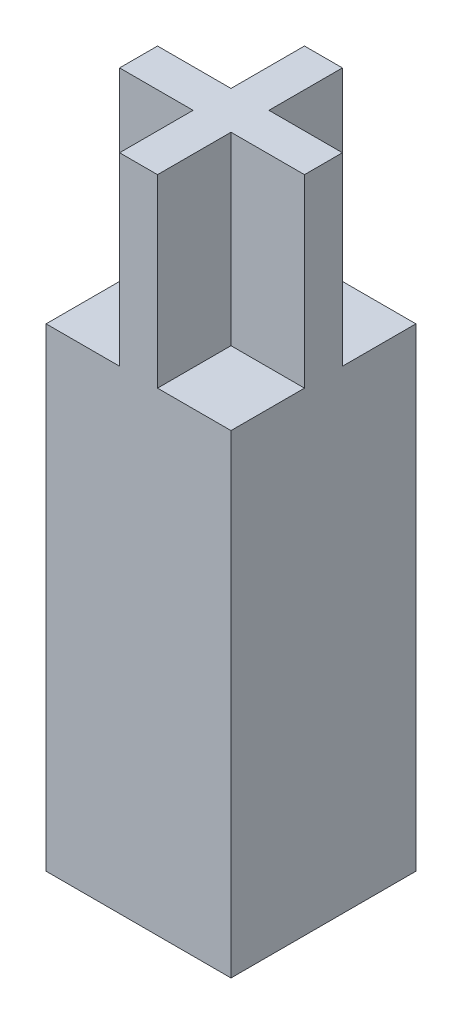
SolidWorks part; units mm, degrees
ref_plane "前视基准面" through (0, 0, 0) normal (0, 0, 1) x (1, 0, 0)
ref_plane "上视基准面" through (0, 0, 0) normal (0, 1, 0) x (1, 0, 0)
ref_plane "右视基准面" through (0, 0, 0) normal (1, 0, 0) x (0, 0, -1)
other "Configuration Table"
sketch "草图5" plane through (0, 0, 0) normal (0, 1, 0) x (-1, 0, 0)
  line L1 (-0.4, -1.95) -> (0.4, -1.95)
  line L2 (-0.4, -1.95) -> (-0.4, 1.95)
  line L3 (-0.4, 1.95) -> (0.4, 1.95)
  line L4 (0.4, -1.95) -> (0.4, 1.95)
  line L5 (-0.4, -1.95) -> (0.4, 1.95) construction
  line L6 (-0.4, 1.95) -> (0.4, -1.95) construction
  line L7 (-1.95, -0.4) -> (1.95, -0.4)
  line L8 (-1.95, -0.4) -> (-1.95, 0.4)
  line L9 (-1.95, 0.4) -> (1.95, 0.4)
  line L10 (1.95, -0.4) -> (1.95, 0.4)
  line L11 (-1.95, -0.4) -> (1.95, 0.4) construction
  line L12 (-1.95, 0.4) -> (1.95, -0.4) construction
  point P0 (0, 0)
  point P6 (0, 0)
  dimension "D1" = 3.9
  dimension "D2" = 0.8
extrude "凸台-拉伸1" add sketch "草图5" along normal blind 3.9 contours L7 L10 L9 L8 | L2 L3 L4 L1
sketch "草图6" plane through (0, 0, 0) normal (0, -1, 0) x (1, 0, 0)
  line L0 (-1.95, 1.95) -> (1.95, -1.95) construction
  line L1 (1.95, -1.95) -> (-1.95, -1.95)
  line L2 (1.95, -1.95) -> (1.95, 1.95)
  line L3 (1.95, 1.95) -> (-1.95, 1.95)
  line L4 (-1.95, -1.95) -> (-1.95, 1.95)
  line L5 (0.4, 1.95) -> (-0.4, 1.95) construction
extrude "凸台-拉伸2" add sketch "草图6" along normal blind 10
